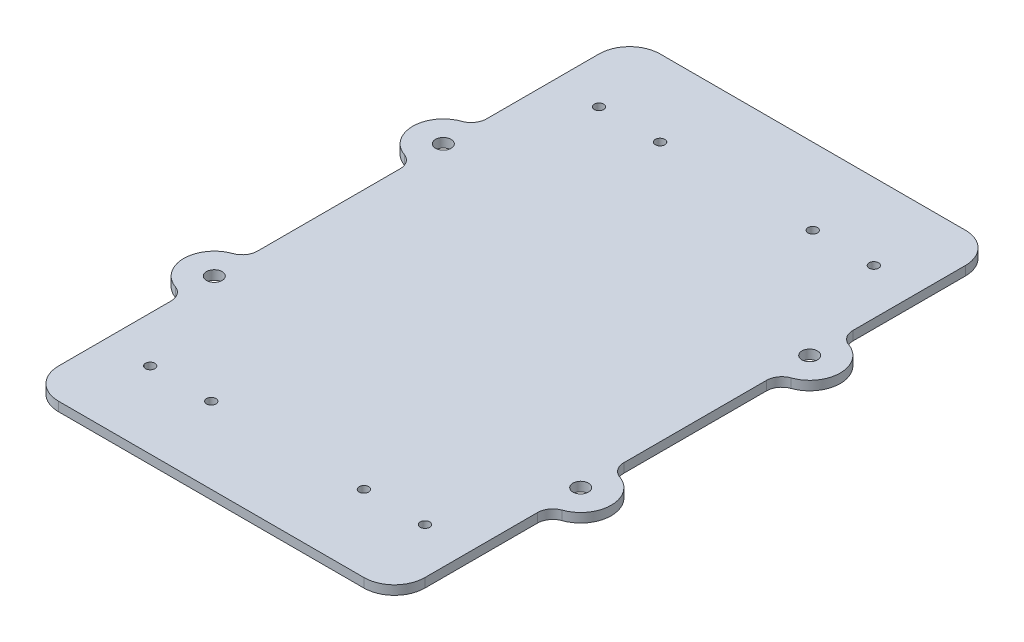
SolidWorks part; units mm, degrees
material "CF-ntbk"
ref_plane "Front Plane" through (0, 0, 0) normal (0, 0, 1) x (1, 0, 0)
ref_plane "Top Plane" through (0, 0, 0) normal (0, 1, 0) x (1, 0, 0)
ref_plane "Right Plane" through (0, 0, 0) normal (1, 0, 0) x (0, 0, -1)
sketch "Sketch1" plane through (0, 0, 0) normal (0, 1, 0) x (1, 0, 0)
  line L0 (-60, 27.5) -> (-60, -27.5)
  line L2 (60, 27.5) -> (60, -27.5)
  line L4 (-44.2539, 0) -> (44.2539, 0) construction
  line L5 (-60, 47.5) -> (-60, 98.5)
  line L7 (-60, 98.5) -> (60, 98.5)
  line L8 (60, 98.5) -> (60, 47.5)
  line L9 (-60, -47.5) -> (-60, -98.5)
  line L10 (-60, -98.5) -> (60, -98.5)
  line L11 (60, -47.5) -> (60, -98.5)
  line L14 (0, -44.7868) -> (0, 44.7868) construction
  arc A0 (-60, 47.5) -> (-60, 27.5) centre (-60, 37.5) ccw
  arc A1 (60, 47.5) -> (60, 27.5) centre (60, 37.5) cw
  arc A2 (60, -27.5) -> (60, -47.5) centre (60, -37.5) cw
  arc A3 (-60, -27.5) -> (-60, -47.5) centre (-60, -37.5) ccw
  circle A4 centre (-60, 37.5) radius 2.55
  circle A5 centre (60, 37.5) radius 2.55
  circle A6 centre (-60, -37.5) radius 2.55
  circle A7 centre (60, -37.5) radius 2.55
  dimension "D1" = 5.1
  dimension "D2" = 10
  dimension "D3" = 55
  dimension "D6" = 120
  dimension "D4" = 37.5
  dimension "D8" = 197
  dimension "D5" = 60
extrude "Boss-Extrude1" add sketch "Sketch1" along normal blind 3
sketch "ConstructionLines" plane through (0, 3, 0) normal (0, 1, 0) x (1, 0, 0)
  line L0 (-52, 91) -> (-52, -91)
  line L1 (-52, -91) -> (52, -91)
  line L2 (52, -91) -> (52, 91)
  line L3 (52, 91) -> (-52, 91)
  line L5 (0, 91) -> (0, -91)
  line L6 (0, -44.7868) -> (0, 44.7868) construction
  line L7 (-52, 0) -> (52, 0)
  line L9 (-44.2539, 0) -> (44.2539, 0) construction
  dimension "D1" = 182
  dimension "D2" = 104
  dimension "D4" = 52
  dimension "D3" = 91
sketch "Sketch2" plane through (0, 3, 0) normal (0, 1, 0) x (1, 0, 0)
  line L0 (60, -98.5) -> (60, -47.5) construction
  line L1 (-60, -98.5) -> (60, -98.5) construction
  line L2 (60, 98.5) -> (-60, 98.5) construction
  circle A0 centre (-45, 73.5) radius 1.55
  circle A1 centre (-25, 73.5) radius 1.55
  circle A2 centre (25, 73.5) radius 1.55
  circle A3 centre (45, 73.5) radius 1.55
  circle A4 centre (-45, -73.5) radius 1.55
  circle A5 centre (-25, -73.5) radius 1.55
  circle A6 centre (25, -73.5) radius 1.55
  circle A7 centre (45, -73.5) radius 1.55
  dimension "D1" = 3.1
  dimension "D2" = 20
  dimension "D3" = 20
  dimension "D4" = 15
  dimension "D5" = 25
  dimension "D6" = 50
  dimension "D7" = 25
extrude "GimbalHoles" cut sketch "Sketch2" against normal up to surface (3 mm away) up to face at (0, 0, 0)
fillet "Fillet1" radius 10 4 edges at (-60, 1.5, 98.5) (60, 1.5, 98.5) (60, 1.5, -98.5) (-60, 1.5, -98.5)
fillet "Fillet2" radius 5 8 edges at (60, 1.5, -47.5) (60, 1.5, -27.5) (60, 1.5, 27.5) (60, 1.5, 47.5) (-60, 1.5, 47.5) (-60, 1.5, 27.5) (-60, 1.5, -27.5) (-60, 1.5, -47.5)
equation "\"ThreadHoleSize\"=5.1"
equation "\"D1@Sketch1\"=\"ThreadHoleSize\""
equation "\"HoleAreaSize\"= 10"
equation "\"D2@Sketch1\"=\"HoleAreaSize\""
equation "\"MidLength\"=172"
equation "\"HoleDist\"=55"
equation "\"D3@Sketch1\"=\"HoleDist\""
equation "\"Width\"=120"
equation "\"D6@Sketch1\"=\"Width\""
equation "\"BatWidth\"=52"
equation "\"D4@ConstructionLines\" = \"BatWidth\""
equation "\"BatLength\"=182"
equation "\"D1@ConstructionLines\"=\"BatLength\""
equation "\"D3@ConstructionLines\"=\"BatLength\"/2"
equation "\"D4@Sketch1\"=\"HoleDist\"/2 +\"HoleAreaSize\""
equation "\"D8@Sketch1\"=\"BatLength\" + 15"
equation "\"GimbalHoleSize\"=3.1"
equation "\"D1@Sketch2\"=\"GimbalHoleSize\""
equation "\"GimbalHoleSep\"=20"
equation "\"D2@Sketch2\"=\"GimbalHoleSep\""
equation "\"D3@Sketch2\"=\"GimbalHoleSep\""
equation "\"GimbalXDIst\"=15.000000"
equation "\"D4@Sketch2\"=\"GimbalXDIst\""
equation "\"GimbalZDist\"=25"
equation "\"D5@Sketch2\"=\"GimbalZDist\""
equation "\"D6@Sketch2\"=\"Width\" - 2 * ( \"GimbalXDIst\" +\"GimbalHoleSep\")"
equation "\"D7@Sketch2\"=\"GimbalZDist\""
equation "\"Depth\"=3.000000"
equation "\"D1@Boss-Extrude1\"=\"Depth\""
equation "\"D5@Sketch1\"=\"Width\"/2"
equation "\"FillRad\"=5.000000"
equation "\"D1@Fillet2\"=\"FillRad\""
